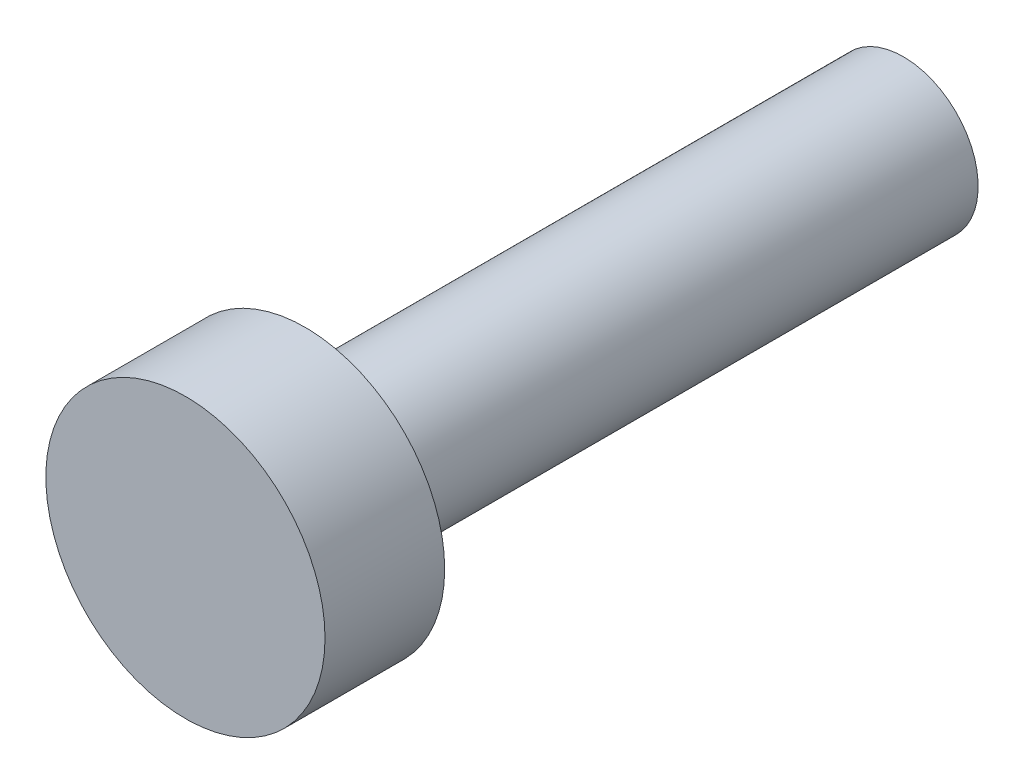
SolidWorks part; units mm, degrees
ref_plane "Plan de face" through (0, 0, 0) normal (0, 0, 1) x (1, 0, 0)
ref_plane "Plan de dessus" through (0, 0, 0) normal (0, 1, 0) x (1, 0, 0)
ref_plane "Plan de droite" through (0, 0, 0) normal (1, 0, 0) x (0, 0, -1)
sketch "Esquisse1" plane through (0, 0, 0) normal (0, 0, 1) x (1, 0, 0)
  circle A0 centre (0, 0) radius 2.8
  dimension "D1" = 5.6
extrude "Boss.-Extru.1" add sketch "Esquisse1" along normal blind 2.4
sketch "Esquisse2" plane through (0, 0, 0) normal (0, 0, -1) x (-1, 0, 0)
  circle A0 centre (0, 0) radius 1.5
  dimension "D1" = 3
extrude "Boss.-Extru.2" add sketch "Esquisse2" along normal blind 12
